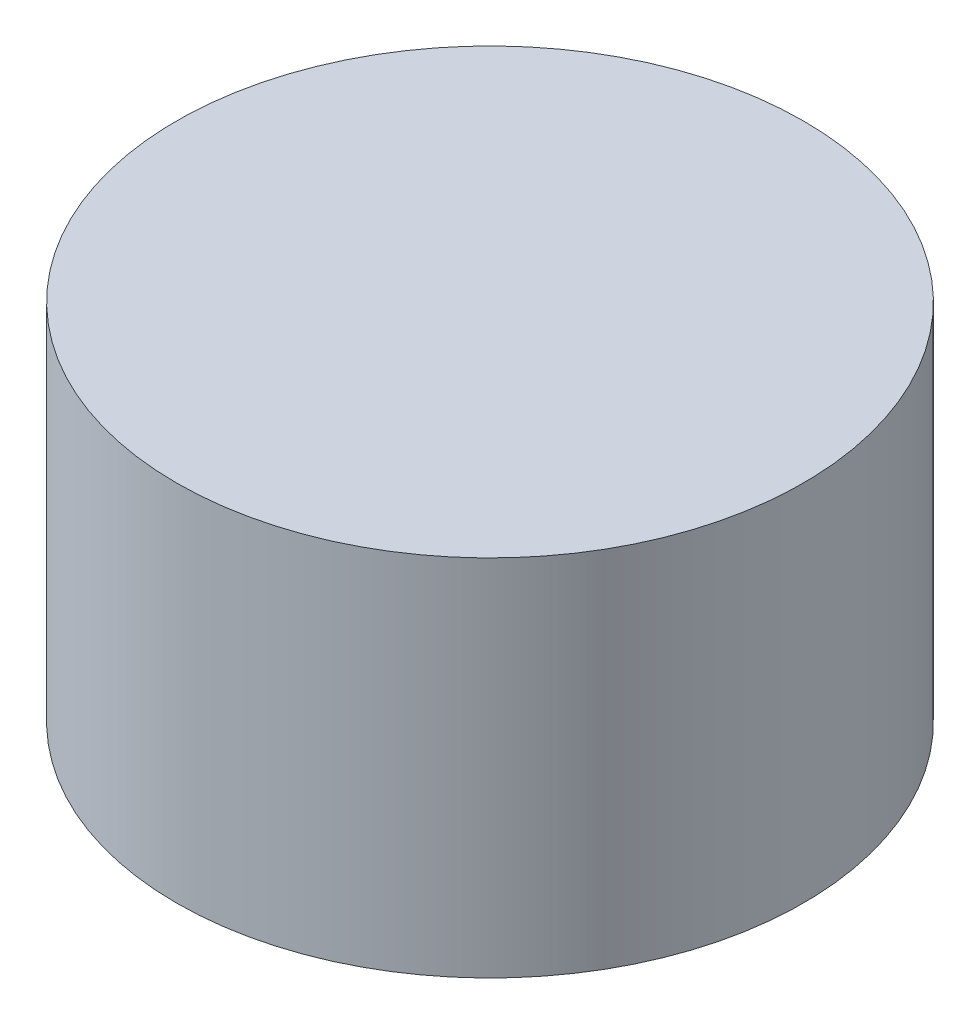
SolidWorks part; units mm, degrees
ref_plane "Front Plane" through (0, 0, 0) normal (0, 0, 1) x (1, 0, 0)
ref_plane "Top Plane" through (0, 0, 0) normal (0, 1, 0) x (1, 0, 0)
ref_plane "Right Plane" through (0, 0, 0) normal (1, 0, 0) x (0, 0, -1)
sketch "Sketch1" plane through (0, 0, 0) normal (0, 1, 0) x (1, 0, 0)
  circle A0 centre (-5.7549, 5.6416) radius 4.3089
  dimension "D1" = 8.6177
extrude "Boss-Extrude1" add sketch "Sketch1" along normal blind 5
